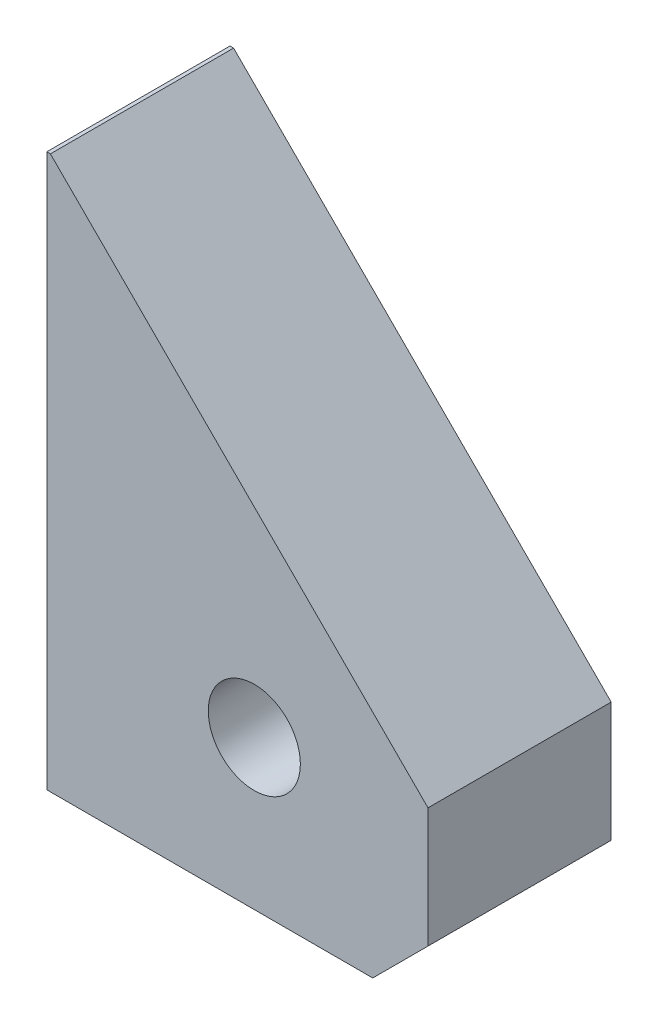
SolidWorks part; units mm, degrees
ref_plane "Спереди" through (0, 0, 0) normal (0, 0, 1) x (1, 0, 0)
ref_plane "Сверху" through (0, 0, 0) normal (0, 1, 0) x (1, 0, 0)
ref_plane "Справа" through (0, 0, 0) normal (1, 0, 0) x (0, 0, -1)
sketch "Эскиз4" plane through (0, 0, 0) normal (0, 1, 0) x (1, 0, 0)
  line L0 (0, 13.4583) -> (36.7459, 13.4583) construction
  line L2 (27.6806, 17.9231) -> (6.9856, 17.9231)
  line L3 (27.6806, 17.9231) -> (27.6806, 7.9774)
  line L4 (27.6806, 7.9774) -> (6.9856, 7.9774)
  line L5 (6.9856, 17.9231) -> (6.9856, 7.9774)
extrude "Вытянуть4" add sketch "Эскиз4" along normal blind 30
chamfer "Фаска1" distance 20.5 angle 45 1 edges at (27.6806, 30, -12.9503)
chamfer "Фаска2" distance 3 angle 45 1 edges at (27.6806, 0, -12.9503)
sketch "Эскиз5" plane through (0, 0, -7.9774) normal (0, 0, 1) x (1, 0, 0)
  circle A0 centre (18.2506, 8.0954) radius 2.5
extrude "Вырез-Вытянуть1" cut sketch "Эскиз5" against normal through all
